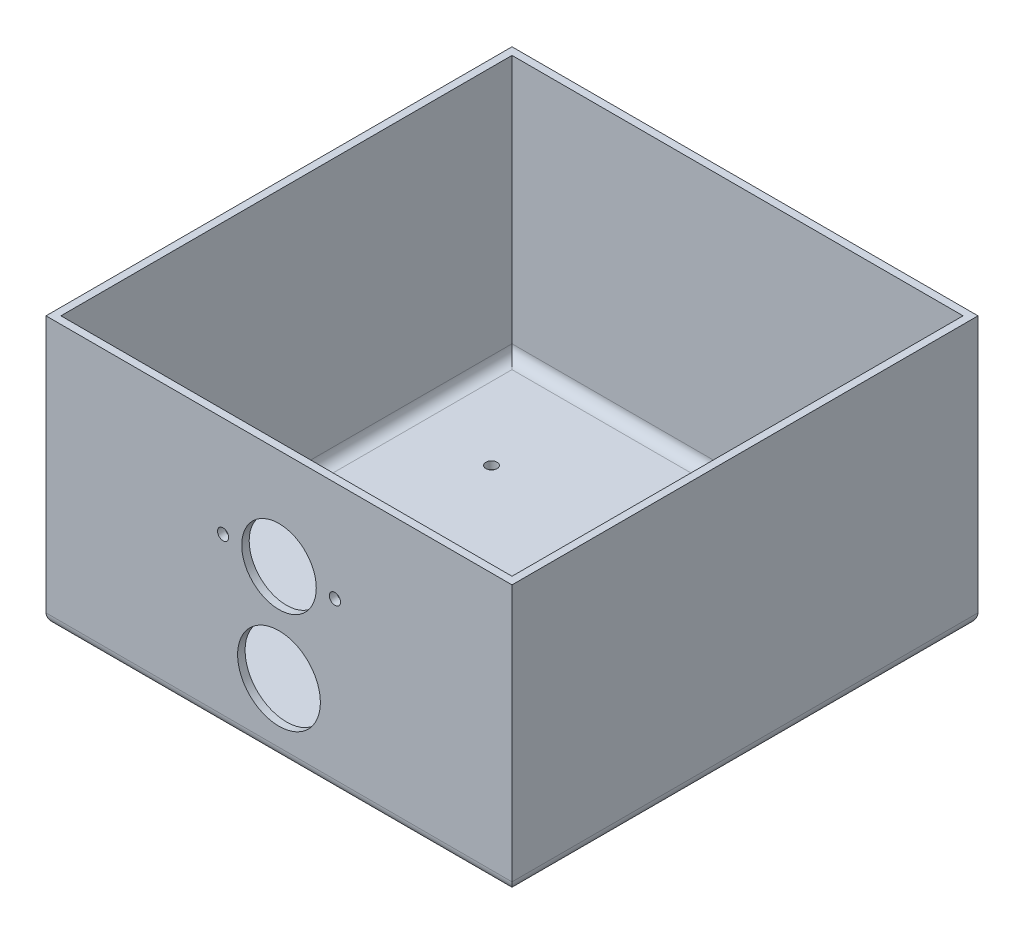
SolidWorks part; units mm, degrees
ref_plane "Front Plane" through (0, 0, 0) normal (0, 0, 1) x (1, 0, 0)
ref_plane "Top Plane" through (0, 0, 0) normal (0, 1, 0) x (1, 0, 0)
ref_plane "Right Plane" through (0, 0, 0) normal (1, 0, 0) x (0, 0, -1)
sketch "Sketch1" plane through (0, 0, 0) normal (0, 1, 0) x (1, 0, 0)
  line L0 (62.5, 62.5) -> (-62.5, 62.5)
  line L1 (60.5, 60.5) -> (-60.5, 60.5)
  line L2 (60.5, 60.5) -> (60.5, -60.5)
  line L3 (60.5, -60.5) -> (-60.5, -60.5)
  line L4 (-60.5, 60.5) -> (-60.5, -60.5)
  line L5 (60.5, 60.5) -> (-60.5, -60.5) construction
  line L6 (60.5, -60.5) -> (-60.5, 60.5) construction
  line L7 (-62.5, 62.5) -> (-62.5, -62.5)
  line L8 (62.5, -62.5) -> (-62.5, -62.5)
  line L9 (62.5, 62.5) -> (62.5, -62.5)
  point P0 (0, 0)
  point P10 (0, 0)
  dimension "D1" = 121
  dimension "D2" = 121
  dimension "D3" = 2
extrude "Boss-Extrude1" add sketch "Sketch1" along normal blind 70
sketch "Sketch2" plane through (0, 0, 0) normal (0, -1, 0) x (1, 0, 0)
  line L0 (-62.5, 62.5) -> (62.5, 62.5) construction
  line L1 (62.5, -62.5) -> (-62.5, -62.5)
  line L2 (62.5, -62.5) -> (62.5, 62.5)
  line L3 (62.5, 62.5) -> (-62.5, 62.5)
  line L4 (-62.5, -62.5) -> (-62.5, 62.5)
  line L5 (62.5, -62.5) -> (-62.5, 62.5) construction
  line L6 (62.5, 62.5) -> (-62.5, -62.5) construction
  point P0 (0, 0)
extrude "Boss-Extrude2" add sketch "Sketch2" along normal blind 2
sketch "Sketch3" plane through (0, -2, 0) normal (0, -1, 0) x (1, 0, 0)
  line L0 (0, 62.5) -> (0, -87.9119) construction
  line L1 (62.5, 62.5) -> (-62.5, 62.5) construction
  line L2 (62.5, -32.5) -> (-77.3231, -32.5) construction
  line L3 (62.5, -62.5) -> (62.5, 62.5) construction
  line L4 (62.5, 32.5) -> (-76.9646, 32.5) construction
  line L5 (-62.5, -62.5) -> (62.5, -62.5) construction
  line L6 (0, 0) -> (-115.9661, 0) construction
  circle A0 centre (38, -32.5) radius 1.5
  circle A1 centre (-38, -32.5) radius 1.5
  circle A2 centre (38, 32.5) radius 1.5
  circle A3 centre (-38, 32.5) radius 1.5
  dimension "D1" = 3
  dimension "D2" = 76
  dimension "D3" = 3
  dimension "D4" = 30
  dimension "D5" = 30
extrude "Cut-Extrude1" cut sketch "Sketch3" against normal blind 3
fillet "Fillet2" radius 3 4 edges at (-62.5, -2, 0) (0, -2, -62.5) (62.5, -2, 0) (0, -2, 62.5)
fillet "Fillet3" radius 3 4 edges at (-60.5, 0, 0) (0, 0, -60.5) (0, 0, 60.5) (60.5, 0, 0)
sketch "Sketch4" plane through (0, 0, 62.5) normal (0, 0, 1) x (1, 0, 0)
  line L0 (0, 70) -> (0, -16.7437) construction
  line L1 (-62.5, 70) -> (62.5, 70) construction
  line L2 (-62.5, 1) -> (62.5, 1) construction
  line L3 (0, 53) -> (-56.9747, 53) construction
  circle A0 centre (0, 17) radius 11.1
  circle A1 centre (0, 43) radius 10
  dimension "D1" = 22.2
  dimension "D2" = 16
  dimension "D3" = 20
  dimension "D4" = 42
extrude "Cut-Extrude2" cut sketch "Sketch4" against normal up to next
sketch "Sketch5" plane through (0, 0, 62.5) normal (0, 0, 1) x (1, 0, 0)
  line L0 (0, 43) -> (-39.1057, 43) construction
  line L1 (0, 43) -> (0, 31.9676) construction
  circle A0 centre (-15, 43) radius 1.5
  circle A1 centre (15, 43) radius 1.5
  dimension "D1" = 3
  dimension "D2" = 30
extrude "Cut-Extrude3" cut sketch "Sketch5" against normal up to next
